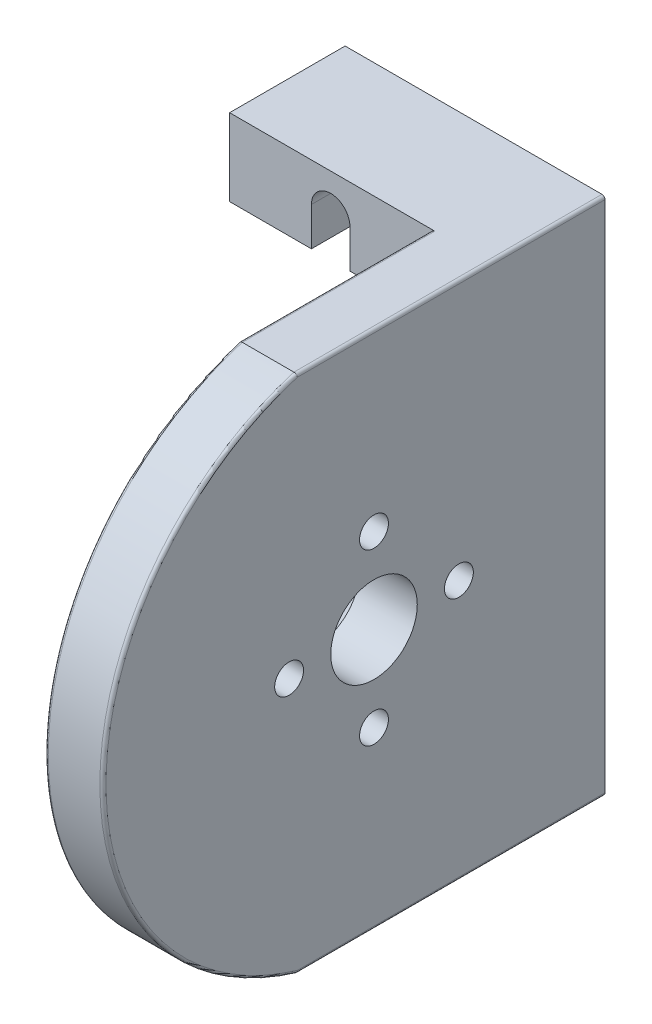
SolidWorks part; units mm, degrees
material "ABS"
ref_plane "Front Plane" through (0, 0, 0) normal (0, 0, 1) x (1, 0, 0)
ref_plane "Top Plane" through (0, 0, 0) normal (0, 1, 0) x (1, 0, 0)
ref_plane "Right Plane" through (0, 0, 0) normal (1, 0, 0) x (0, 0, -1)
sketch "Sketch2" plane through (0, 0, 0) normal (0, 0, 1) x (1, 0, 0)
  line L0 (0, 0) -> (0, 6.35)
  line L1 (0, 6.35) -> (16.6687, 6.35)
  line L2 (16.6687, 6.35) -> (16.6687, 36.5125)
  line L3 (16.6687, 21.4312) -> (21.4312, 21.4312) construction
  line L4 (21.4312, 42.8625) -> (21.4312, 0)
  line L5 (21.4312, 0) -> (0, 0)
  line L6 (21.4312, 42.8625) -> (0, 42.8625)
  line L7 (0, 36.5125) -> (16.6687, 36.5125)
  line L8 (0, 42.8625) -> (0, 36.5125)
  dimension "D1" = 4.7625
  dimension "D2" = 16.6687
  dimension "D3" = 30.1625
  dimension "D4" = 6.35
extrude "Boss-Extrude1" add sketch "Sketch2" along normal blind 25.4
sketch "Sketch3" plane through (21.4312, 0, 0) normal (1, 0, 0) x (0, 0, -1)
  line L1 (0, 0) -> (0, 42.8625) construction
  line L2 (-25.4, 0) -> (-25.4, 42.8625) construction
  circle A0 centre (-19.05, 21.4312) radius 3.5687
  point P9 (0, 21.4312)
  dimension "D1" = 7.1374
  dimension "D2" = 6.35
extrude "Cut-Extrude1" cut sketch "Sketch3" against normal up to next
sketch "Sketch4" plane through (0, 0, 25.4) normal (0, 0, 1) x (1, 0, 0)
  line L0 (16.6688, 21.4312) -> (21.4312, 21.4312) construction
  line L1 (16.6687, 36.5125) -> (16.6687, 6.35) construction
  line L2 (21.4312, 0) -> (21.4312, 42.8625) construction
  line L3 (16.6687, 6.35) -> (0, 6.35) construction
  line L4 (9.9219, 3.1812) -> (9.9219, 6.35)
  line L5 (6.7469, 3.1812) -> (6.7469, 6.35)
  line L6 (6.7469, 36.5125) -> (9.9219, 36.5125)
  line L7 (6.7469, 39.6812) -> (6.7469, 36.5125)
  line L8 (6.7469, 6.35) -> (9.9219, 6.35)
  line L9 (9.9219, 39.6812) -> (9.9219, 36.5125)
  arc A0 (6.7469, 3.1812) -> (9.9219, 3.1812) centre (8.3344, 3.1812) ccw
  arc A2 (6.7469, 39.6812) -> (9.9219, 39.6812) centre (8.3344, 39.6812) cw
  point P19 (8.3344, 6.35)
  dimension "D1" = 3.175
  dimension "D2" = 36.5
extrude "Cut-Extrude2" cut sketch "Sketch4" against normal up to next
sketch "Sketch5" plane through (0, 0, 25.4) normal (0, 0, 1) x (1, 0, 0)
  line L0 (0, 0) -> (21.4312, 0) construction
  line L1 (0, 42.8625) -> (16.6687, 42.8625)
  line L2 (0, 42.8625) -> (0, 0)
  line L3 (0, 0) -> (16.6688, 0)
  line L4 (16.6687, 42.8625) -> (16.6688, 0)
  line L5 (16.6687, 36.5125) -> (16.6687, 6.35) construction
extrude "Cut-Extrude3" cut sketch "Sketch5" against normal blind 15.875
sketch "Sketch6" plane through (21.4312, 0, 0) normal (1, 0, 0) x (0, 0, -1)
  line L4 (-25.4, 0) -> (-25.4, 42.8625) construction
  line L5 (-25.4, 0) -> (-25.4, 42.8625)
  circle A1 centre (-19.05, 21.4312) radius 22.3522
  line M6 (-25.4, 42.8625) -> (-25.4, 0)
extrude "Boss-Extrude2" add sketch "Sketch6" against normal up to surface (4.7625 mm away) contours A1 M6
sketch "Sketch9" plane through (21.4312, 0, 0) normal (1, 0, 0) x (0, 0, -1)
  circle A0 centre (-12.05, 21.4312) radius 1.1906
  circle A2 centre (-19.05, 14.4313) radius 1.1906
  circle A3 centre (-26.05, 21.4312) radius 1.1906
  circle A4 centre (-19.05, 28.4312) radius 1.1906
  point P4 (-19.05, 21.4312)
  dimension "D1" = 2.3813
  dimension "D2" = 7
  dimension "D3" = 4
extrude "Cut-Extrude5" cut sketch "Sketch9" against normal up to next
fillet "Fillet1" radius 0.254 6 edges at (16.6687, 42.8625, 17.4625) (21.4312, 42.8625, 12.7) (21.4312, 0, 12.7) (16.6688, 0, 17.4625) (21.4312, 21.4312, 41.4022) (16.6688, 21.4312, 41.4022)
fillet "Fillet2" radius 1.5875 2 edges at (16.6688, 6.35, 4.7625) (16.6687, 36.5125, 4.7625)
